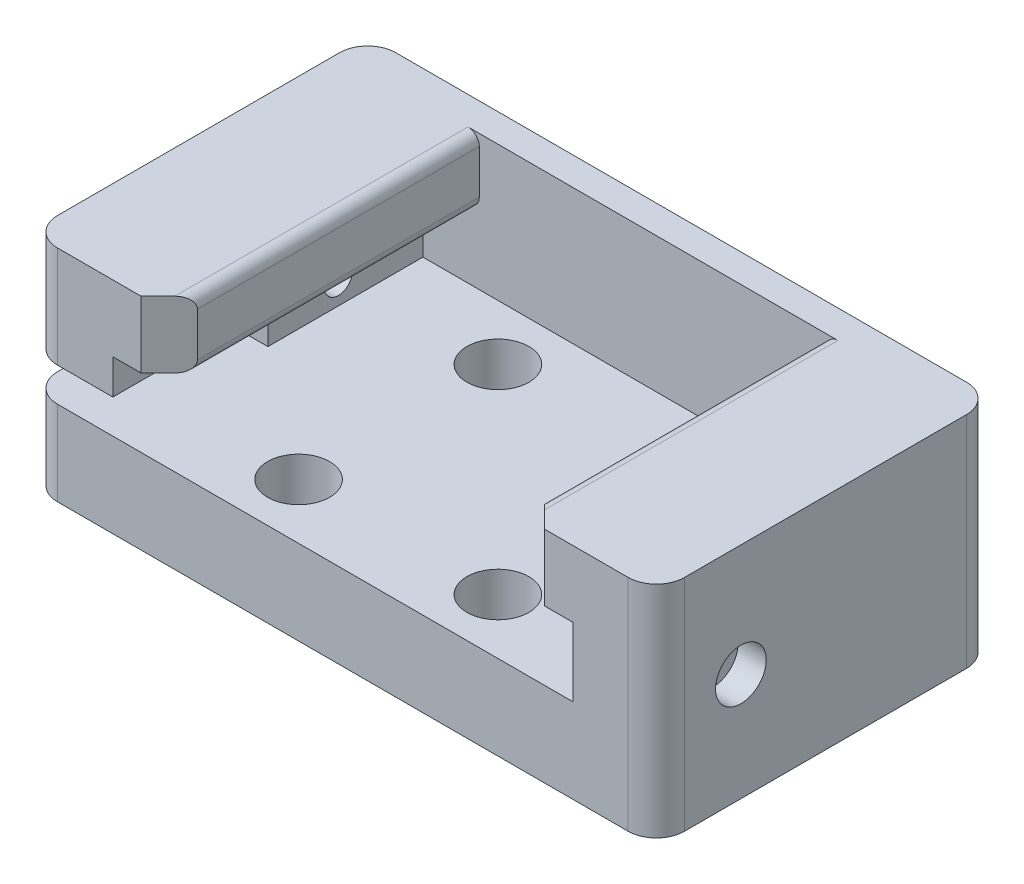
SolidWorks part; units mm, degrees
ref_plane "Piano frontale" through (0, 0, 0) normal (0, 0, 1) x (1, 0, 0)
ref_plane "Piano superiore" through (0, 0, 0) normal (0, 1, 0) x (1, 0, 0)
ref_plane "Piano destro" through (0, 0, 0) normal (1, 0, 0) x (0, 0, -1)
sketch "Schizzo2" plane through (0, 0, 0) normal (0, 1, 0) x (1, 0, 0)
  line L1 (-55.6, -27.5) -> (55.6, -27.5)
  line L2 (-55.6, -27.5) -> (-55.6, 27.5)
  line L3 (-55.6, 27.5) -> (55.6, 27.5)
  line L4 (55.6, -27.5) -> (55.6, 27.5)
  line L5 (-55.6, -27.5) -> (55.6, 27.5) construction
  line L6 (-55.6, 27.5) -> (55.6, -27.5) construction
  point P0 (0, 0)
  dimension "D1" = 55
  dimension "D2" = 111.2
extrude "Estrusione-Estrusione1" add sketch "Schizzo2" along normal blind 15
sketch "Schizzo3" plane through (0, 15, 0) normal (0, 1, 0) x (1, 0, 0)
  line L0 (-8.25, 0) -> (8.25, 0) construction
  line L1 (40.8, 27.5) -> (55.6, 27.5)
  line L2 (40.8, 27.5) -> (40.8, -27.5)
  line L3 (40.8, -27.5) -> (55.6, -27.5)
  line L4 (55.6, 27.5) -> (55.6, -27.5)
  line L5 (40.8, 27.5) -> (55.6, -27.5) construction
  line L6 (40.8, -27.5) -> (55.6, 27.5) construction
  line L7 (55.6, -27.5) -> (55.6, 27.5) construction
  line L8 (-55.6, -27.5) -> (55.6, -27.5) construction
  point P0 (48.2, 0)
  dimension "D1" = 14.8
extrude "Estrusione-Estrusione2" add sketch "Schizzo3" along normal blind 24
sketch "Schizzo4" plane through (40.8, 0, 0) normal (-1, 0, 0) x (0, 0, 1)
  line L0 (0, -8.25) -> (0, 8.25) construction
  line L1 (-27.5, 27.2) -> (27.5, 27.2)
  line L2 (-27.5, 27.2) -> (-27.5, 39)
  line L3 (-27.5, 39) -> (27.5, 39)
  line L4 (27.5, 27.2) -> (27.5, 39)
  line L5 (-27.5, 27.2) -> (27.5, 39) construction
  line L6 (-27.5, 39) -> (27.5, 27.2) construction
  line L7 (-27.5, 39) -> (27.5, 39) construction
  line L8 (27.5, 39) -> (27.5, 15) construction
  point P0 (0, 33.1)
  dimension "D1" = 11.8
extrude "Estrusione-Estrusione3" add sketch "Schizzo4" along normal blind 10
chamfer "Smusso1" distance 5 angle 45 1 edges at (30.8, 33.1, 27.5)
mirror "Specchia2" about plane through (0, 0, 0) normal (1, 0, 0) of "Estrusione-Estrusione2"
mirror "Specchia3" about plane through (0, 0, 0) normal (1, 0, 0) of "Estrusione-Estrusione3"
chamfer "Smusso2" distance 5 angle 45 1 edges at (-30.8, 33.1, 27.5)
sketch "Schizzo8" plane through (0, 15, 0) normal (0, 1, 0) x (1, 0, 0)
  line L0 (0, 0) -> (17.6777, 17.6777)
  line L2 (0, -21.45) -> (0, 21.45) construction
  circle A0 centre (0, 0) radius 25
  point P7 (17.6777, 17.6777)
  dimension "D1" = 50
  dimension "D2" = 45
hole_wizard "Foro Ø6.0 (6)-1" positions "Schizzo8" profile "Schizzo9" hole size "Ø6.0" standard "ISO" end condition through all
sketch "Schizzo9" plane through (17.6777, 15, -17.6777) normal (1, 0, 0) x (0, 0, 1)
  line L0 (0, 0) -> (0, 15)
  line L1 (0, 15) -> (3, 15)
  line L2 (3, 15) -> (3, 0)
  line L5 (3, 0) -> (0, 0)
  line L11 (0, -6.35) -> (0, 107.95) construction
  dimension "Thru Hole Dia." = 6
  dimension "Thru Hole Depth" = 15
mirror "Specchia10" about plane through (0, 0, 0) normal (0, 0, 1) of "Foro Ø6.0 (6)-1"
mirror "Specchia11" about plane through (0, 0, 0) normal (1, 0, 0) of "Specchia10", "Foro Ø6.0 (6)-1"
sketch "Schizzo10" plane through (0, 15, 0) normal (0, 1, 0) x (1, 0, 0)
  circle A0 centre (17.6777, 17.6777) radius 5.5
  dimension "D1" = 11
extrude "Taglio-Estrusione3" cut sketch "Schizzo10" against normal blind 9
mirror "Specchia12" about plane through (0, 0, 0) normal (0, 0, 1) of "Taglio-Estrusione3"
mirror "Specchia13" about plane through (0, 0, 0) normal (1, 0, 0) of "Specchia12", "Taglio-Estrusione3"
fillet "Raccordo1" radius 2 4 edges at (-30.8, 27.2, -2.5) (-30.8, 39, -2.5) (30.8, 27.2, -2.5) (30.8, 39, -2.5)
ref_plane "Plane1" through (-40.6, 25, 22.5) normal (0, 0, -1) x (-1, 0, 0)
sketch "Sketch2" plane through (-55.6, 0, 0) normal (-1, 0, 0) x (0, 0, 1)
  line L0 (-27.5, 15) -> (27.5, 15) construction
  line L1 (-27.5, 15) -> (27.5, 15) construction
  line L2 (0, -21.45) -> (0, 21.45) construction
  line L3 (0, 15) -> (27.5, 15)
  line L4 (0, 15) -> (0, 21)
  line L5 (0, 21) -> (27.5, 21)
  line L6 (27.5, 15) -> (27.5, 21)
  line L7 (27.5, 39) -> (27.5, 0) construction
  dimension "D1" = 6
extrude "Cut-Extrude1" cut sketch "Sketch2" against normal up to next
sketch "Sketch3" plane through (0, 0, -27.5) normal (0, 0, -1) x (-1, 0, 0)
  line L0 (55.6, 39) -> (55.6, 0) construction
  line L1 (-55.6, 39) -> (55.6, 39)
  line L2 (-55.6, 39) -> (-55.6, 0)
  line L3 (-55.6, 0) -> (55.6, 0)
  line L4 (55.6, 39) -> (55.6, 0)
  line L5 (34.65, 0) -> (-34.65, 0) construction
extrude "Boss-Extrude1" add sketch "Sketch3" along normal blind 5
sketch "Sketch5" plane through (0, 0, 0) normal (0, -1, 0) x (1, 0, 0)
  circle A0 centre (17.6777, -17.6777) radius 3 construction
  circle A1 centre (-17.6777, -17.6777) radius 3 construction
  circle A2 centre (-17.6777, 17.6777) radius 3 construction
  circle A3 centre (17.6777, 17.6777) radius 3 construction
  circle A4 centre (17.6777, -17.6777) radius 3 construction
  circle A5 centre (-17.6777, -17.6777) radius 3 construction
  circle A6 centre (-17.6777, 17.6777) radius 3 construction
  circle A7 centre (17.6777, 17.6777) radius 3 construction
  circle A8 centre (0, 0) radius 25 construction
  circle A9 centre (0, 0) radius 15.6
  dimension "D1" = 31.2
extrude "Boss-Extrude2" add sketch "Sketch5" along normal blind 5.9
fillet "Fillet1" radius 1 1 edges at (0, -5.9, -15.6)
fillet "Fillet2" radius 5 5 edges at (55.6, 19.5, 27.5) (55.6, 19.5, -32.5) (-55.6, 7.5, 27.5) (-55.6, 30, 27.5) (-55.6, 19.5, -32.5)
sketch "Schizzo11" plane through (0, 0, 0) normal (0, -1, 0) x (1, 0, 0)
  circle A0 centre (0, 0) radius 25 construction
  circle A1 centre (0, -25) radius 2.9
  circle A2 centre (-25, 0) radius 2.9
  dimension "D1" = 5.8
  dimension "D2" = 5.8
extrude "Estrusione-Estrusione4" add sketch "Schizzo11" along normal blind 5.9
fillet "Raccordo2" radius 1 2 edges at (0, -5.9, -27.9) (-25, -5.9, -2.9)
sketch "Sketch6" plane through (-55.6, 0, 0) normal (-1, 0, 0) x (0, 0, 1)
  line L0 (-27.5, 15) -> (27.5, 15) construction
  line L1 (-27.5, 15) -> (27.5, 15) construction
  line L2 (-27.5, 15) -> (-12.5, 15) construction
  line L3 (-12.5, 15) -> (-12.5, 19.1) construction
  circle A0 centre (-12.5, 19.1) radius 2.5
  dimension "D3" = 5
  dimension "D1" = 4.1
  dimension "D2" = 15
extrude "Cut-Extrude2" cut sketch "Sketch6" against normal up to next
sketch "Sketch7" plane through (55.6, 0, 0) normal (1, 0, 0) x (0, 0, -1)
  line L0 (27.5, 15) -> (-27.5, 15) construction
  line L1 (27.5, 15) -> (-27.5, 15) construction
  line L2 (-27.5, 15) -> (-12.5, 15) construction
  line L3 (-12.5, 15) -> (-12.5, 19.1) construction
  circle A0 centre (-12.5, 19.1) radius 2.5
  dimension "D3" = 5
  dimension "D1" = 15
  dimension "D2" = 4.1
extrude "Cut-Extrude3" cut sketch "Sketch7" against normal up to next
sketch "Sketch8" plane through (-55.6, 0, 0) normal (-1, 0, 0) x (0, 0, 1)
  circle A0 centre (-12.5, 19.1) radius 4.5
  dimension "D1" = 9
extrude "Cut-Extrude4" cut sketch "Sketch8" against normal blind 5
sketch "Sketch9" plane through (55.6, 0, 0) normal (1, 0, 0) x (0, 0, -1)
  circle A0 centre (-12.5, 19.1) radius 4.5
  dimension "D1" = 9
extrude "Cut-Extrude5" cut sketch "Sketch9" against normal blind 5
